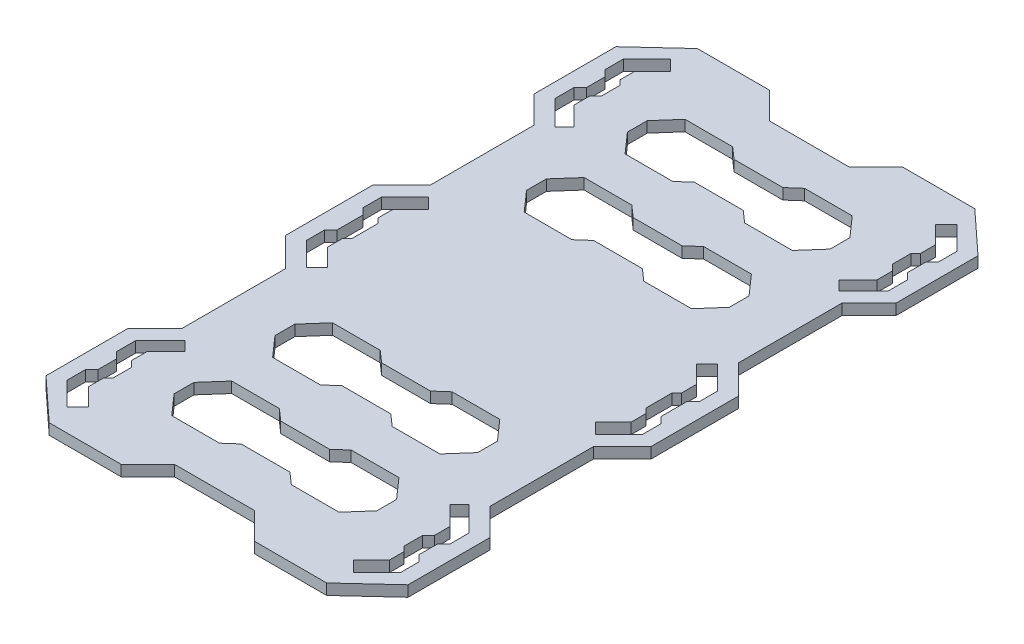
SolidWorks part; units mm, degrees
material "Thornel Mat VMA"
ref_plane "Front Plane" through (0, 0, 0) normal (0, 0, 1) x (1, 0, 0)
ref_plane "Top Plane" through (0, 0, 0) normal (0, 1, 0) x (1, 0, 0)
ref_plane "Right Plane" through (0, 0, 0) normal (1, 0, 0) x (0, 0, -1)
sketch "Sketch2" plane through (0, 0, 0) normal (0, 1, 0) x (1, 0, 0)
  line L0 (22, 238.4881) -> (246, 238.4881) construction
  line L2 (7.3967, 54.8514) -> (-7.3967, 54.8514)
  line L3 (-7.3967, 54.8514) -> (-12.3127, 59.7675)
  line L4 (-12.3127, 59.7675) -> (-25.5839, 59.7675)
  line L5 (-25.5839, 59.7675) -> (-33.3877, 52.5529)
  line L6 (-33.3877, 52.5529) -> (-33.3877, 37.4182)
  line L7 (-33.3877, 37.4182) -> (-28.4053, 32.4359)
  line L8 (-28.4053, 32.4359) -> (-28.4053, 13.3967)
  line L9 (-28.4053, 13.3967) -> (-33.7097, 8.0924)
  line L10 (-33.7097, 8.0924) -> (-33.7097, 0)
  line L12 (-28.4053, -13.3967) -> (-33.7097, -8.0924)
  line L13 (-28.4053, -32.4359) -> (-28.4053, -13.3967)
  line L14 (-33.3877, -37.4182) -> (-28.4053, -32.4359)
  line L15 (-33.3877, -52.5529) -> (-33.3877, -37.4182)
  line L16 (-25.5839, -59.7675) -> (-33.3877, -52.5529)
  line L17 (-12.3127, -59.7675) -> (-25.5839, -59.7675)
  line L18 (-7.3967, -54.8514) -> (-12.3127, -59.7675)
  line L19 (7.3967, -54.8514) -> (-7.3967, -54.8514)
  line L20 (-33.7097, 0) -> (-33.7097, -8.0924)
  line L21 (33.7097, 0) -> (33.7097, -8.0924)
  line L22 (7.3967, -54.8514) -> (12.3127, -59.7675)
  line L23 (12.3127, -59.7675) -> (25.5839, -59.7675)
  line L24 (25.5839, -59.7675) -> (33.3877, -52.5529)
  line L25 (33.3877, -52.5529) -> (33.3877, -37.4182)
  line L26 (33.3877, -37.4182) -> (28.4053, -32.4359)
  line L27 (28.4053, -32.4359) -> (28.4053, -13.3967)
  line L28 (28.4053, -13.3967) -> (33.7097, -8.0924)
  line L29 (33.7097, 8.0924) -> (33.7097, 0)
  line L30 (28.4053, 13.3967) -> (33.7097, 8.0924)
  line L31 (28.4053, 32.4359) -> (28.4053, 13.3967)
  line L32 (33.3877, 37.4182) -> (28.4053, 32.4359)
  line L33 (33.3877, 52.5529) -> (33.3877, 37.4182)
  line L34 (25.5839, 59.7675) -> (33.3877, 52.5529)
  line L35 (12.3127, 59.7675) -> (25.5839, 59.7675)
  line L36 (7.3967, 54.8514) -> (12.3127, 59.7675)
  point P26 (0, -54.8514)
sketch "Sketch3" plane through (0, 0, 0) normal (0, 1, 0) x (1, 0, 0)
  line L0 (-26.4124, 55.6115) -> (-24.4345, 53.6336)
  line L1 (-24.4345, 53.6336) -> (-27.7174, 50.3506)
  line L2 (-27.7174, 50.3506) -> (-27.7174, 47.6181)
  line L3 (-27.7174, 47.6181) -> (-26.8406, 46.7413)
  line L4 (-26.8406, 46.7413) -> (-26.8406, 43.336)
  line L5 (-26.8406, 43.336) -> (-27.9316, 42.245)
  line L6 (-27.9316, 42.245) -> (-27.9316, 39.3801)
  line L7 (-27.9316, 39.3801) -> (-24.4345, 35.883)
  line L8 (-24.4345, 35.883) -> (-26.183, 34.1344)
  line L9 (-26.183, 34.1344) -> (-30.7354, 38.6868)
  line L10 (-30.7354, 38.6868) -> (-30.7354, 42.1839)
  line L11 (-30.7354, 42.1839) -> (-29.5832, 43.336)
  line L12 (-29.5832, 43.336) -> (-29.5832, 46.7413)
  line L13 (-29.5832, 46.7413) -> (-30.7354, 47.8934)
  line L14 (-30.7354, 47.8934) -> (-30.7354, 51.2886)
  line L15 (-30.7354, 51.2886) -> (-26.4124, 55.6115)
sketch "Sketch4" plane through (0, 0, 0) normal (0, 1, 0) x (1, 0, 0)
  line L0 (-26.6647, 11.2712) -> (-24.6868, 9.2932)
  line L1 (-24.6868, 9.2932) -> (-27.9698, 6.0102)
  line L2 (-27.9698, 6.0102) -> (-27.9698, 3.2778)
  line L3 (-27.9698, 3.2778) -> (-27.0929, 2.401)
  line L13 (-29.8356, 2.401) -> (-30.9877, 3.5531)
  line L14 (-30.9877, 3.5531) -> (-30.9877, 6.9482)
  line L15 (-30.9877, 6.9482) -> (-26.6647, 11.2712)
  line L19 (-27.0929, 2.401) -> (-27.0929, 0)
  line L20 (-27.0929, 0) -> (-29.8356, 0)
  line L21 (-29.8356, 0) -> (-29.8356, 2.401)
sketch "Sketch5" plane through (0, 0, 0) normal (0, 1, 0) x (1, 0, 0)
  line L12 (-18.6894, 39.9743) -> (-18.6894, 43.6271)
  line L13 (-18.6894, 43.6271) -> (-15.4211, 47.3278)
  line L14 (-15.4211, 47.3278) -> (-6.6258, 47.3278)
  line L15 (-6.6258, 47.3278) -> (-4.5033, 45.4534)
  line L16 (-4.5033, 45.4534) -> (4.5033, 45.4534)
  line L17 (6.6258, 47.3278) -> (4.5033, 45.4534)
  line L18 (15.4211, 47.3278) -> (6.6258, 47.3278)
  line L19 (18.6894, 43.6271) -> (15.4211, 47.3278)
  line L20 (18.6894, 39.9743) -> (18.6894, 43.6271)
  line L21 (18.6894, 39.9743) -> (15.4211, 36.2735)
  line L22 (15.4211, 36.2735) -> (6.6258, 36.2735)
  line L23 (6.6258, 36.2735) -> (4.5033, 38.148)
  line L24 (-4.5033, 38.148) -> (4.5033, 38.148)
  line L25 (-6.6258, 36.2735) -> (-4.5033, 38.148)
  line L26 (-15.4211, 36.2735) -> (-6.6258, 36.2735)
  line L27 (-18.6894, 39.9743) -> (-15.4211, 36.2735)
  point P14 (18.6894, 41.8007)
ref_plane "Plane1" through (0, 0, -32.5) normal (0, 0, 1) x (1, 0, 0)
ref_plane "Plane2" through (0, 2, 0) normal (0, 1, 0) x (1, 0, 0)
sketch "Sketch6" plane through (0, 2, 0) normal (0, 1, 0) x (1, 0, 0)
  line L0 (22, 238.4881) -> (246, 238.4881) construction
  line L2 (7.3967, 54.8514) -> (-7.3967, 54.8514)
  line L3 (-7.3967, 54.8514) -> (-12.3127, 59.7675)
  line L4 (-12.3127, 59.7675) -> (-25.5839, 59.7675)
  line L5 (-25.5839, 59.7675) -> (-33.3877, 52.5529)
  line L6 (-33.3877, 52.5529) -> (-33.3877, 37.4182)
  line L7 (-33.3877, 37.4182) -> (-28.4053, 32.4359)
  line L8 (-28.4053, 32.4359) -> (-28.4053, 13.3967)
  line L9 (-28.4053, 13.3967) -> (-33.7097, 8.0924)
  line L10 (-33.7097, 8.0924) -> (-33.7097, 0)
  line L12 (-28.4053, -13.3967) -> (-33.7097, -8.0924)
  line L13 (-28.4053, -32.4359) -> (-28.4053, -13.3967)
  line L14 (-33.3877, -37.4182) -> (-28.4053, -32.4359)
  line L15 (-33.3877, -52.5529) -> (-33.3877, -37.4182)
  line L16 (-25.5839, -59.7675) -> (-33.3877, -52.5529)
  line L17 (-12.3127, -59.7675) -> (-25.5839, -59.7675)
  line L18 (-7.3967, -54.8514) -> (-12.3127, -59.7675)
  line L19 (7.3967, -54.8514) -> (-7.3967, -54.8514)
  line L20 (-33.7097, 0) -> (-33.7097, -8.0924)
  line L21 (33.7097, 0) -> (33.7097, -8.0924)
  line L22 (7.3967, -54.8514) -> (12.3127, -59.7675)
  line L23 (12.3127, -59.7675) -> (25.5839, -59.7675)
  line L24 (25.5839, -59.7675) -> (33.3877, -52.5529)
  line L25 (33.3877, -52.5529) -> (33.3877, -37.4182)
  line L26 (33.3877, -37.4182) -> (28.4053, -32.4359)
  line L27 (28.4053, -32.4359) -> (28.4053, -13.3967)
  line L28 (28.4053, -13.3967) -> (33.7097, -8.0924)
  line L29 (33.7097, 8.0924) -> (33.7097, 0)
  line L30 (28.4053, 13.3967) -> (33.7097, 8.0924)
  line L31 (28.4053, 32.4359) -> (28.4053, 13.3967)
  line L32 (33.3877, 37.4182) -> (28.4053, 32.4359)
  line L33 (33.3877, 52.5529) -> (33.3877, 37.4182)
  line L34 (25.5839, 59.7675) -> (33.3877, 52.5529)
  line L35 (12.3127, 59.7675) -> (25.5839, 59.7675)
  line L36 (7.3967, 54.8514) -> (12.3127, 59.7675)
  point P26 (0, -54.8514)
loft "Loft1" add profiles "Sketch6", "Sketch2"
extrude "Cut-Extrude1" cut sketch "Sketch3" against normal through all both and the other way through all
extrude "Cut-Extrude2" cut sketch "Sketch4" against normal through all both and the other way through all
extrude "Cut-Extrude3" cut sketch "Sketch5" against normal through all both and the other way through all
mirror "Mirror1" about plane through (0, 0, -32.5) normal (0, 0, 1) of "Cut-Extrude3"
mirror "Mirror2" about plane through (0, 0, 0) normal (0, 0, 1) of "Cut-Extrude3", "Mirror1"
mirror "Mirror3" about plane through (0, 0, 0) normal (1, 0, 0) of "Cut-Extrude1"
mirror "Mirror4" about plane through (0, 0, 0) normal (0, 0, 1) of "Cut-Extrude2"
mirror "Mirror5" about plane through (0, 0, 0) normal (0, 0, 1) of "Cut-Extrude1", "Mirror3"
mirror "Mirror6" about plane through (0, 0, 0) normal (1, 0, 0) of "Mirror4", "Cut-Extrude2"
